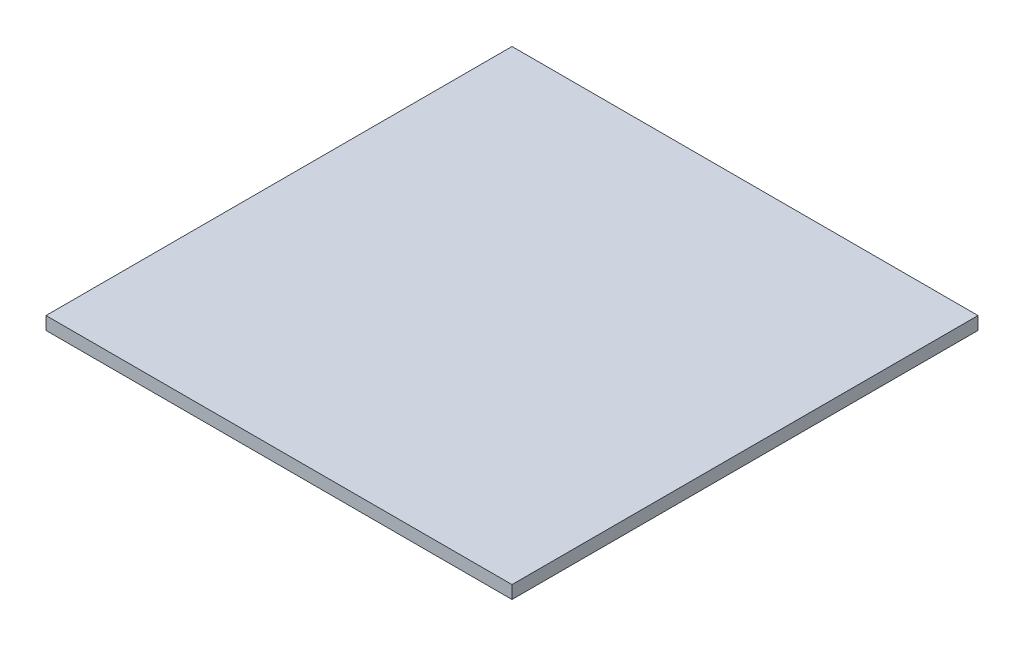
SolidWorks part; units mm, degrees
ref_plane "Front Plane" through (0, 0, 0) normal (0, 0, 1) x (1, 0, 0)
ref_plane "Top Plane" through (0, 0, 0) normal (0, 1, 0) x (1, 0, 0)
ref_plane "Right Plane" through (0, 0, 0) normal (1, 0, 0) x (0, 0, -1)
sketch "Sketch1" plane through (0, 0, 0) normal (0, 1, 0) x (1, 0, 0)
  line L1 (0, 0) -> (457.2, 0)
  line L2 (0, 0) -> (0, 457.2)
  line L3 (0, 457.2) -> (457.2, 457.2)
  line L4 (457.2, 0) -> (457.2, 457.2)
  dimension "D1" = 457.2
  dimension "D2" = 457.2
extrude "Boss-Extrude1" add sketch "Sketch1" along normal blind 12.7
